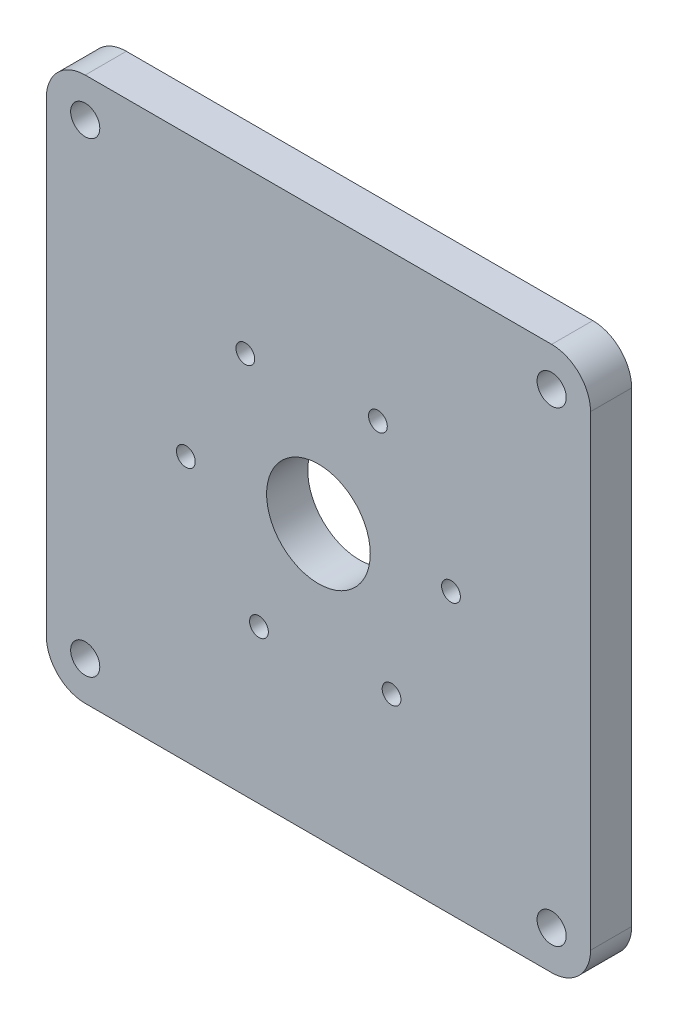
SolidWorks part; units mm, degrees
material "Aleación 6061"
ref_plane "Alzado" through (0, 0, 0) normal (0, 0, 1) x (1, 0, 0)
ref_plane "Planta" through (0, 0, 0) normal (0, 1, 0) x (1, 0, 0)
ref_plane "Vista lateral" through (0, 0, 0) normal (1, 0, 0) x (0, 0, -1)
sketch "Croquis1" plane through (0, 0, 0) normal (0, 0, 1) x (1, 0, 0)
  line L0 (-36, -42) -> (36, -42)
  line L1 (42, -36) -> (42, 36)
  line L2 (36, 42) -> (-36, 42)
  line L3 (-42, 36) -> (-42, -36)
  arc A0 (36, -42) -> (42, -36) centre (36, -36) ccw
  arc A1 (42, 36) -> (36, 42) centre (36, 36) ccw
  arc A2 (-36, 42) -> (-42, 36) centre (-36, 36) ccw
  arc A3 (-42, -36) -> (-36, -42) centre (-36, -36) ccw
  dimension "D1" = 6
  dimension "D2" = 6
  dimension "D3" = 6
  dimension "D4" = 6
  dimension "D5" = 36
  dimension "D6" = 42
  dimension "D7" = 36
  dimension "D8" = 42
  dimension "D9" = 42
  dimension "D10" = 36
  dimension "D11" = 42
  dimension "D12" = 36
  dimension "D13" = 36
  dimension "D14" = 42
  dimension "D15" = 36
  dimension "D16" = 42
  dimension "D17" = 42
  dimension "D18" = 36
  dimension "D19" = 42
  dimension "D20" = 36
extrude "Placa_soporte_M1" add sketch "Croquis1" along normal blind 6.35 from offset 36.5
sketch "Croquis2" plane through (0, 0, 0) normal (0, 0, 1) x (1, 0, 0)
  circle A0 centre (-36, -36) radius 2.25
  circle A1 centre (-36, 36) radius 2.25
  circle A2 centre (36, -36) radius 2.25
  circle A3 centre (36, 36) radius 2.25
  circle A4 centre (20.4639, 1.2158) radius 1.45
  circle A5 centre (9.1791, 18.3302) radius 1.45
  circle A6 centre (-11.2849, 17.1144) radius 1.45
  circle A7 centre (-20.4639, -1.2158) radius 1.45
  circle A8 centre (-9.1791, -18.3302) radius 1.45
  circle A9 centre (11.2849, -17.1144) radius 1.45
  circle A10 centre (0, 0) radius 8
  dimension "D1" = 4.5
  dimension "D2" = 4.5
  dimension "D3" = 4.5
  dimension "D4" = 4.5
  dimension "D5" = 2.9
  dimension "D6" = 2.9
  dimension "D7" = 2.9
  dimension "D8" = 2.9
  dimension "D9" = 2.9
  dimension "D10" = 2.9
  dimension "D11" = 16
  dimension "D12" = 36
  dimension "D13" = 36
  dimension "D14" = 36
  dimension "D15" = 36
  dimension "D16" = 36
  dimension "D17" = 36
  dimension "D18" = 36
  dimension "D19" = 36
  dimension "D20" = 20.4639
  dimension "D21" = 1.2158
  dimension "D22" = 9.1791
  dimension "D23" = 18.3302
  dimension "D24" = 11.2849
  dimension "D25" = 17.1144
  dimension "D26" = 20.4639
  dimension "D27" = 1.2158
  dimension "D28" = 9.1791
  dimension "D29" = 18.3302
  dimension "D30" = 11.2849
  dimension "D31" = 17.1144
extrude "Barrenos_separadores_y_motor" cut sketch "Croquis2" along normal blind 6.35 from offset 36.5
sketch "Croquis3" plane through (0, 0, 0) normal (0, 0, 1) x (1, 0, 0)
  circle A0 centre (20.4639, 1.2158) radius 2.5
  circle A1 centre (9.1791, 18.3302) radius 2.5
  circle A2 centre (-11.2849, 17.1144) radius 2.5
  circle A3 centre (-20.4639, -1.2158) radius 2.5
  circle A4 centre (-9.1791, -18.3302) radius 2.5
  circle A5 centre (11.2849, -17.1144) radius 2.5
  dimension "D1" = 5
  dimension "D2" = 5
  dimension "D3" = 5
  dimension "D4" = 5
  dimension "D5" = 5
  dimension "D6" = 5
  dimension "D7" = 20.4639
  dimension "D8" = 1.2158
  dimension "D9" = 9.1791
  dimension "D10" = 18.3302
  dimension "D11" = 11.2849
  dimension "D12" = 17.1144
  dimension "D13" = 20.4639
  dimension "D14" = 1.2158
  dimension "D15" = 9.1791
  dimension "D16" = 18.3302
  dimension "D17" = 11.2849
  dimension "D18" = 17.1144
extrude "Refrentado_M2-5" cut sketch "Croquis3" along normal blind 2.6 from offset 36.5
